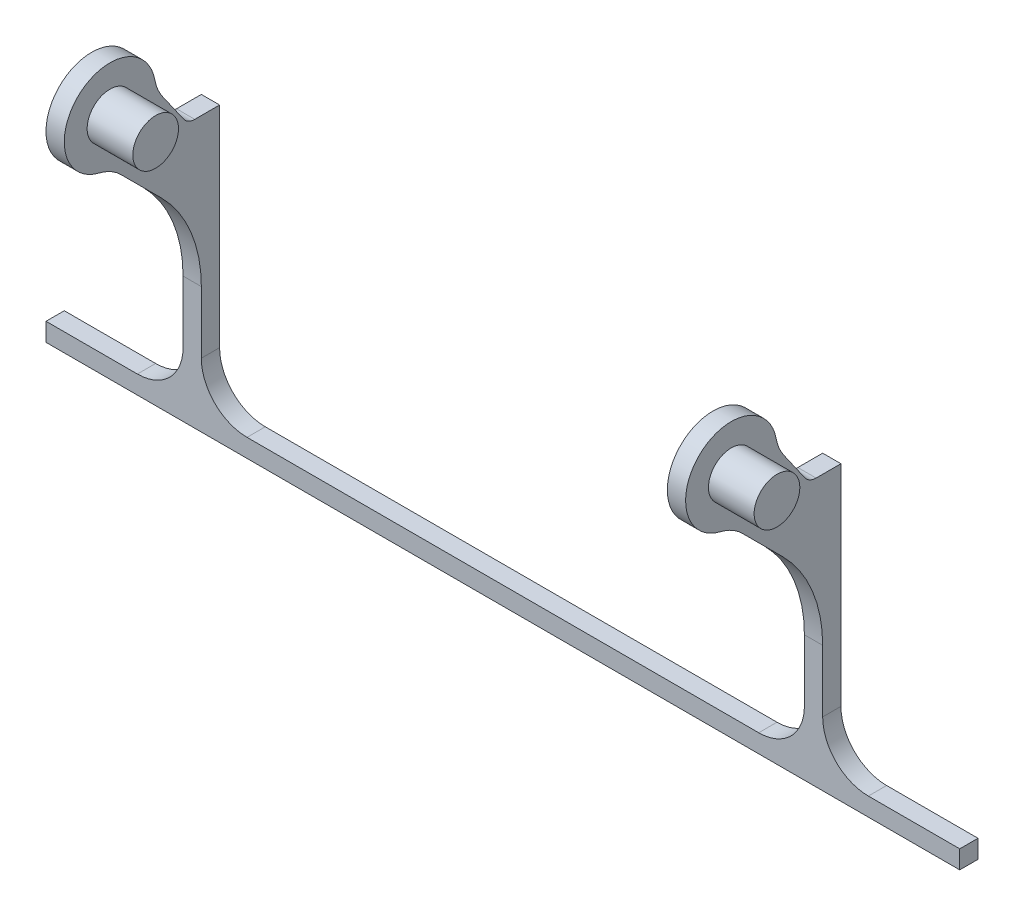
SolidWorks part; units mm, degrees
ref_plane "Plan de face" through (0, 0, 0) normal (0, 0, 1) x (1, 0, 0)
ref_plane "Plan de dessus" through (0, 0, 0) normal (0, 1, 0) x (1, 0, 0)
ref_plane "Plan de droite" through (0, 0, 0) normal (1, 0, 0) x (0, 0, -1)
sketch "Esquisse1" plane through (0, 0, 0) normal (0, 0, 1) x (1, 0, 0)
  line L2 (100, -160) -> (-100, -160) construction
  line L4 (-100, -160) -> (-100, -156) construction
  line L5 (-100, -156) -> (-70, -156) construction
  line L6 (-70, -156) -> (-70, -100) construction
  line L7 (-70, -100) -> (-66, -100) construction
  line L8 (-66, -100) -> (-66, -156) construction
  line L9 (-66, -156) -> (66, -156) construction
  line L10 (66, -156) -> (66, -100) construction
  line L11 (66, -100) -> (70, -100) construction
  line L12 (70, -100) -> (70, -156) construction
  line L13 (70, -156) -> (100, -156) construction
  line L17 (-70, -110) -> (-66, -110) construction
  line L19 (66, -110) -> (70, -110) construction
  line L21 (-70, -110) -> (-66, -110)
  line L22 (-66, -110) -> (-66, -156)
  line L23 (-66, -156) -> (66, -156)
  line L24 (66, -156) -> (66, -110)
  line L25 (66, -110) -> (70, -110)
  line L26 (70, -110) -> (70, -156)
  line L27 (70, -156) -> (100, -156)
  line L28 (100, -156) -> (100, -160)
  line L29 (100, -160) -> (-100, -160)
  line L30 (-100, -160) -> (-100, -156)
  line L31 (-100, -156) -> (-70, -156)
  line L32 (-70, -156) -> (-70, -110)
  point P20 (-100, -95.0546)
  point P26 (-100, -103.5413)
  dimension "D1" = 4
  dimension "D2" = 4
  dimension "D3" = 4
  dimension "D4" = 4
  dimension "D5" = 4
extrude "Boss.-Extru.1" add sketch "Esquisse1" against normal blind 4
sketch "Esquisse2" plane through (70, 0, 0) normal (1, 0, 0) x (0, 0, -1)
  line L0 (0, -110) -> (-20, -110) construction
  line L1 (-20, -110) -> (-20, -90) construction
  line L2 (4, -110) -> (-10, -90) construction
  line L3 (0, -110) -> (0, -120) construction
  line L4 (0, -156) -> (0, -110) construction
  line L5 (0, -120) -> (-20, -100) construction
  line L6 (0, -120) -> (-20, -100)
  line L7 (4, -110) -> (-10, -90)
  line L8 (0, -120) -> (0, -110)
  line L9 (0, -110) -> (4, -110)
  arc A0 (-10, -90) -> (-20, -100) centre (-20, -90) ccw
  dimension "D3" = 20
  dimension "D1" = 20
  dimension "D2" = 20
  dimension "D4" = 10
extrude "Boss.-Extru.2" add sketch "Esquisse2" against normal blind 4
sketch "Esquisse3" plane through (-70, 0, 0) normal (-1, 0, 0) x (0, 0, 1)
  line L0 (-4, -110) -> (10, -90) construction
  line L1 (20, -100) -> (0, -120) construction
  line L2 (-4, -110) -> (10, -90)
  line L3 (20, -100) -> (0, -120)
  line L4 (-4, -110) -> (0, -110)
  line L5 (0, -110) -> (0, -120)
  arc A0 (20, -100) -> (10, -90) centre (20, -90) ccw construction
  arc A1 (20, -100) -> (10, -90) centre (20, -90) ccw
extrude "Boss.-Extru.3" add sketch "Esquisse3" against normal blind 4
fillet "Congé1" radius 30 2 edges at (68, -120, 0) (-68, -120, 0)
fillet "Congé2" radius 30 2 edges at (-68, -110, -4) (68, -110, -4)
fillet "Congé3" radius 10 4 edges at (66, -156, -2) (-66, -156, -2) (-70, -156, -2) (70, -156, -2)
sketch "Esquisse4" plane through (-70, 0, 0) normal (-1, 0, 0) x (0, 0, 1)
  line L0 (-4, -119.4567) -> (-4, -100)
  line L1 (-4, -100) -> (3, -100)
  line L2 (10, -90) -> (1.423, -102.2528) construction
  line L3 (3, -100) -> (-4, -119.4567)
extrude "Boss.-Extru.4" add sketch "Esquisse4" against normal blind 4
ref_plane "Plan1" through (-66, -100, 3) normal (0, 0, -1) x (-1, 0, 0)
sketch "Esquisse6" plane through (70, 0, 0) normal (1, 0, 0) x (0, 0, -1)
  line L0 (4, -119.4567) -> (4, -100)
  line L1 (4, -100) -> (-3, -100)
  line L2 (-3, -100) -> (4, -119.4567)
extrude "Boss.-Extru.5" add sketch "Esquisse6" against normal blind 4
sketch "Esquisse7" plane through (70, 0, 0) normal (1, 0, 0) x (0, 0, -1)
  line L0 (4, -100) -> (-20, -100) construction
  line L1 (-20, -100) -> (-20, -90) construction
  circle A0 centre (-20, -90) radius 5
  dimension "D1" = 10
extrude "Boss.-Extru.6" add sketch "Esquisse7" along normal blind 10
sketch "Esquisse9" plane through (-70, 0, 0) normal (-1, 0, 0) x (0, 0, 1)
  line L0 (-4, -100) -> (20, -100) construction
  line L1 (20, -100) -> (20, -90) construction
  circle A0 centre (20, -90) radius 5
  dimension "D1" = 10
extrude "Boss.-Extru.7" add sketch "Esquisse9" against normal blind 14
fillet "Congé4" radius 10 4 edges at (-68, -100, 20) (-68, -90, 10) (68, -90, 10) (68, -100, 20)
fillet "Congé5" radius 3 2 edges at (-68, -100, 3) (68, -100, 3)
